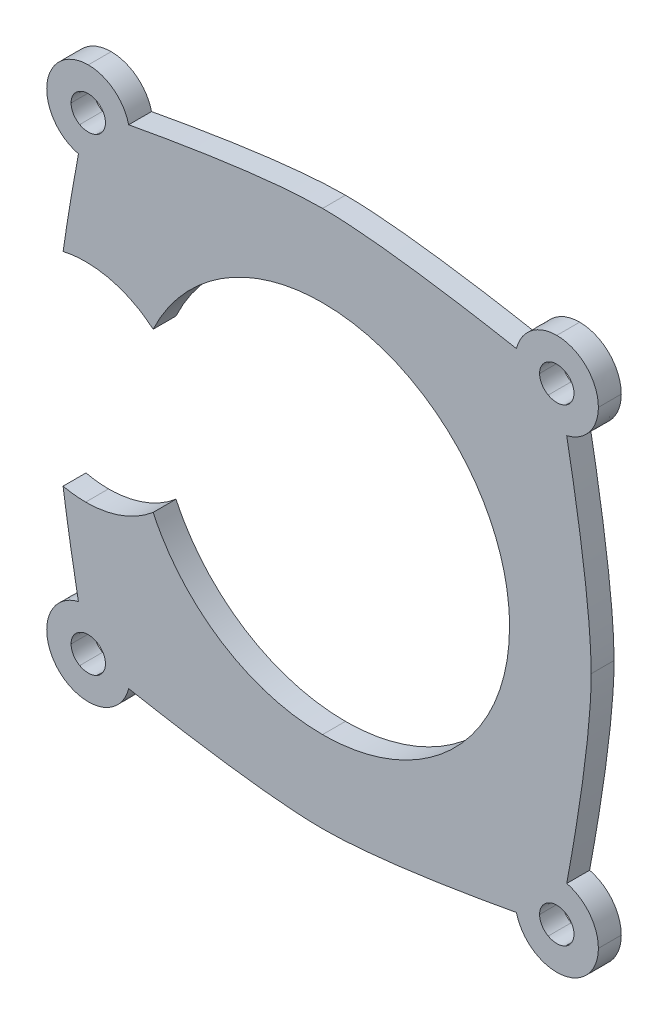
SolidWorks part; units mm, degrees
ref_plane "Front Plane" through (0, 0, 0) normal (0, 0, 1) x (1, 0, 0)
ref_plane "Top Plane" through (0, 0, 0) normal (0, 1, 0) x (1, 0, 0)
ref_plane "Right Plane" through (0, 0, 0) normal (1, 0, 0) x (0, 0, -1)
sketch "Model" plane through (0, 0, 0) normal (0, 0, 1) x (1, 0, 0)
  spline S58 degree 3 poles (89.2351, 300.7571) (86.0499, 300.7571) (83.4672, 298.1744) (83.4672, 294.9892) knots 0 0 0 0 1 1 1 1
  spline S59 degree 3 poles (83.4672, 294.9892) (83.4672, 292.2738) (85.3412, 290.0015) (87.8681, 289.3888) knots 0 0 0 0 1 1 1 1
  spline S60 degree 3 poles (87.8681, 289.3888) (87.222, 285.9203) (86.4117, 281.2869) (85.7426, 276.583) knots 0 0 0 0 1 1 1 1
  spline S61 degree 3 poles (85.7426, 276.583) (86.7484, 276.8046) (87.7923, 276.9269) (88.8647, 276.9269) knots 0 0 0 0 1 1 1 1
  spline S62 degree 3 poles (88.8647, 276.9269) (92.4395, 276.9269) (95.7088, 275.6291) (98.231, 273.4785) knots 0 0 0 0 1 1 1 1
  spline S63 degree 3 poles (98.231, 273.4785) (102.3717, 282.3112) (111.3436, 288.4275) (121.7436, 288.4275) knots 0 0 0 0 1 1 1 1
  spline S64 degree 3 poles (121.7436, 288.4275) (136.0771, 288.4275) (147.6904, 276.8142) (147.6904, 262.4807) knots 0 0 0 0 1 1 1 1
  spline S65 degree 3 poles (147.6904, 262.4807) (147.6904, 248.1472) (136.0771, 236.5251) (121.7436, 236.5251) knots 0 0 0 0 1 1 1 1
  spline S66 degree 3 poles (121.7436, 236.5251) (111.3448, 236.5251) (102.3723, 242.6431) (98.231, 251.474) knots 0 0 0 0 1 1 1 1
  spline S67 degree 3 poles (98.231, 251.474) (95.709, 249.3223) (92.4388, 248.0256) (88.8647, 248.0256) knots 0 0 0 0 1 1 1 1
  spline S68 degree 3 poles (88.8647, 248.0256) (87.7892, 248.0256) (86.7423, 248.1555) (85.7338, 248.3784) knots 0 0 0 0 1 1 1 1
  spline S69 degree 3 poles (85.7338, 248.3784) (86.4009, 243.6743) (87.2136, 239.0421) (87.8593, 235.5726) knots 0 0 0 0 1 1 1 1
  spline S70 degree 3 poles (87.8593, 235.5726) (85.3363, 234.9571) (83.4672, 232.6848) (83.4672, 229.9722) knots 0 0 0 0 1 1 1 1
  spline S71 degree 3 poles (83.4672, 229.9722) (83.4672, 226.787) (86.0499, 224.2043) (89.2351, 224.2043) knots 0 0 0 0 1 1 1 1
  spline S72 degree 3 poles (89.2351, 224.2043) (91.9477, 224.2043) (94.22, 226.0733) (94.8355, 228.5964) knots 0 0 0 0 1 1 1 1
  spline S73 degree 3 poles (94.8355, 228.5964) (102.0476, 227.2542) (114.2854, 225.2009) (121.7436, 225.2009) knots 0 0 0 0 1 1 1 1
  spline S74 degree 3 poles (121.7436, 225.2009) (129.2018, 225.2009) (141.4396, 227.2542) (148.6517, 228.5964) knots 0 0 0 0 1 1 1 1
  spline S75 degree 3 poles (148.6517, 228.5964) (149.2674, 226.0736) (151.5397, 224.2043) (154.2521, 224.2043) knots 0 0 0 0 1 1 1 1
  spline S76 degree 3 poles (154.2521, 224.2043) (157.4373, 224.2043) (160.02, 226.787) (160.02, 229.9722) knots 0 0 0 0 1 1 1 1
  spline S77 degree 3 poles (160.02, 229.9722) (160.02, 232.6825) (158.1478, 234.9548) (155.6279, 235.5726) knots 0 0 0 0 1 1 1 1
  spline S78 degree 3 poles (155.6279, 235.5726) (156.9701, 242.7847) (159.0234, 255.0225) (159.0234, 262.4807) knots 0 0 0 0 1 1 1 1
  spline S79 degree 3 poles (159.0234, 262.4807) (159.0234, 269.9389) (156.9701, 282.1767) (155.6279, 289.3888) knots 0 0 0 0 1 1 1 1
  spline S80 degree 3 poles (155.6279, 289.3888) (158.1476, 290.0067) (160.02, 292.279) (160.02, 294.9892) knots 0 0 0 0 1 1 1 1
  spline S81 degree 3 poles (160.02, 294.9892) (160.02, 298.1744) (157.4373, 300.7571) (154.2521, 300.7571) knots 0 0 0 0 1 1 1 1
  spline S82 degree 3 poles (154.2521, 300.7571) (151.5419, 300.7571) (149.2696, 298.8846) (148.6517, 296.365) knots 0 0 0 0 1 1 1 1
  spline S83 degree 3 poles (148.6517, 296.365) (141.4396, 297.7072) (129.2018, 299.7605) (121.7436, 299.7605) knots 0 0 0 0 1 1 1 1
  spline S84 degree 3 poles (121.7436, 299.7605) (114.2839, 299.7605) (102.0463, 297.6993) (94.8355, 296.3562) knots 0 0 0 0 1 1 1 1
  spline S85 degree 3 poles (94.8355, 296.3562) (94.2208, 298.8803) (91.9485, 300.7571) (89.2351, 300.7571) knots 0 0 0 0 1 1 1 1
  spline S86 degree 3 poles (91.6166, 294.9867) (91.6166, 294.1619) (91.1619, 293.3997) (90.4237, 292.9873) knots 0 0 0 0 1 1 1 1
  spline S87 degree 3 poles (90.4237, 292.9873) (89.6856, 292.5748) (88.7761, 292.5748) (88.038, 292.9873) knots 0 0 0 0 1 1 1 1
  spline S88 degree 3 poles (88.038, 292.9873) (87.2998, 293.3997) (86.8451, 294.1619) (86.8451, 294.9867) knots 0 0 0 0 1 1 1 1
  spline S89 degree 3 poles (86.8451, 294.9867) (86.8451, 295.8115) (87.2998, 296.5737) (88.038, 296.9861) knots 0 0 0 0 1 1 1 1
  spline S90 degree 3 poles (88.038, 296.9861) (88.7761, 297.3985) (89.6856, 297.3985) (90.4237, 296.9861) knots 0 0 0 0 1 1 1 1
  spline S91 degree 3 poles (90.4237, 296.9861) (91.1619, 296.5737) (91.6166, 295.8115) (91.6166, 294.9867) knots 0 0 0 0 1 1 1 1
  spline S92 degree 3 poles (156.6352, 229.9682) (156.6352, 229.1433) (156.1804, 228.3812) (155.4423, 227.9687) knots 0 0 0 0 1 1 1 1
  spline S93 degree 3 poles (155.4423, 227.9687) (154.7041, 227.5563) (153.7946, 227.5563) (153.0565, 227.9687) knots 0 0 0 0 1 1 1 1
  spline S94 degree 3 poles (153.0565, 227.9687) (152.3183, 228.3812) (151.8636, 229.1433) (151.8636, 229.9682) knots 0 0 0 0 1 1 1 1
  spline S95 degree 3 poles (151.8636, 229.9682) (151.8636, 230.793) (152.3183, 231.5552) (153.0565, 231.9676) knots 0 0 0 0 1 1 1 1
  spline S96 degree 3 poles (153.0565, 231.9676) (153.7946, 232.38) (154.7041, 232.38) (155.4423, 231.9676) knots 0 0 0 0 1 1 1 1
  spline S97 degree 3 poles (155.4423, 231.9676) (156.1804, 231.5552) (156.6352, 230.793) (156.6352, 229.9682) knots 0 0 0 0 1 1 1 1
  spline S98 degree 3 poles (91.6166, 229.9682) (91.6166, 229.1433) (91.1619, 228.3812) (90.4237, 227.9687) knots 0 0 0 0 1 1 1 1
  spline S99 degree 3 poles (90.4237, 227.9687) (89.6856, 227.5563) (88.7761, 227.5563) (88.038, 227.9687) knots 0 0 0 0 1 1 1 1
  spline S100 degree 3 poles (88.038, 227.9687) (87.2998, 228.3812) (86.8451, 229.1433) (86.8451, 229.9682) knots 0 0 0 0 1 1 1 1
  spline S101 degree 3 poles (86.8451, 229.9682) (86.8451, 230.793) (87.2998, 231.5552) (88.038, 231.9676) knots 0 0 0 0 1 1 1 1
  spline S102 degree 3 poles (88.038, 231.9676) (88.7761, 232.38) (89.6856, 232.38) (90.4237, 231.9676) knots 0 0 0 0 1 1 1 1
  spline S103 degree 3 poles (90.4237, 231.9676) (91.1619, 231.5552) (91.6166, 230.793) (91.6166, 229.9682) knots 0 0 0 0 1 1 1 1
  spline S104 degree 3 poles (156.6352, 294.9867) (156.6352, 294.1619) (156.1804, 293.3997) (155.4423, 292.9873) knots 0 0 0 0 1 1 1 1
  spline S105 degree 3 poles (155.4423, 292.9873) (154.7041, 292.5748) (153.7946, 292.5748) (153.0565, 292.9873) knots 0 0 0 0 1 1 1 1
  spline S106 degree 3 poles (153.0565, 292.9873) (152.3183, 293.3997) (151.8636, 294.1619) (151.8636, 294.9867) knots 0 0 0 0 1 1 1 1
  spline S107 degree 3 poles (151.8636, 294.9867) (151.8636, 295.8115) (152.3183, 296.5737) (153.0565, 296.9861) knots 0 0 0 0 1 1 1 1
  spline S108 degree 3 poles (153.0565, 296.9861) (153.7946, 297.3985) (154.7041, 297.3985) (155.4423, 296.9861) knots 0 0 0 0 1 1 1 1
  spline S109 degree 3 poles (155.4423, 296.9861) (156.1804, 296.5737) (156.6352, 295.8115) (156.6352, 294.9867) knots 0 0 0 0 1 1 1 1
extrude "Boss-Extrude1" add sketch "Model" along normal blind 3.175 contours S73 S74 S75 S76 S77 S78 S79 S80 S81 S82 S83 S84 S85 S58 S59 S60 S61 S62 S63 S64 S65 S66 S67 S68 S69 S70 S71 S72 | S99 S100 S101 S102 S103 S98 | S87 S88 S89 S90 S91 S86 | S105 S106 S107 S108 S109 S104 | S93 S94 S95 S96 S97 S92
